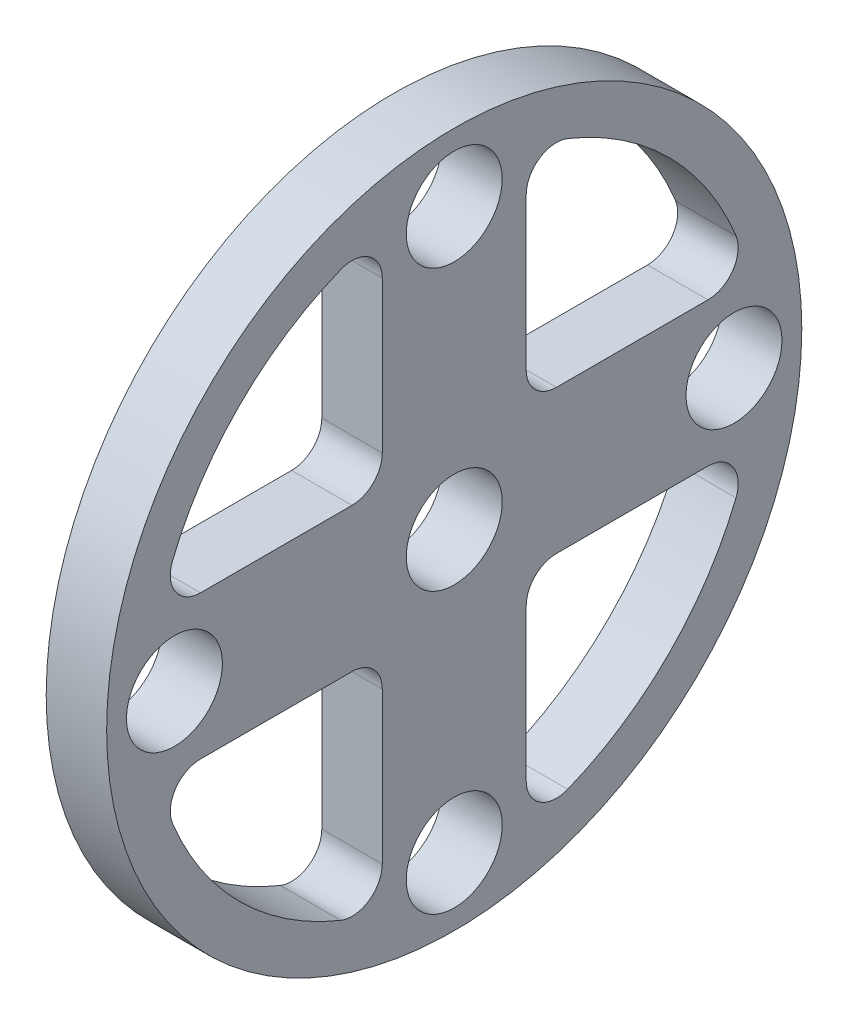
SolidWorks part; units mm, degrees
ref_plane "Front Plane" through (0, 0, 0) normal (0, 0, 1) x (1, 0, 0)
ref_plane "Top Plane" through (0, 0, 0) normal (0, 1, 0) x (1, 0, 0)
ref_plane "Right Plane" through (0, 0, 0) normal (1, 0, 0) x (0, 0, -1)
sketch "Sketch1" plane through (0, 0, 0) normal (1, 0, 0) x (0, 0, -1)
  line L0 (0, 0) -> (0, 1.0694) construction
  line L1 (4.7625, 6.7625) -> (4.7625, 16.7892)
  line L2 (16.7892, 4.7625) -> (6.7625, 4.7625)
  line L3 (6.7625, -4.7625) -> (16.7892, -4.7625)
  line L4 (4.7625, -16.7892) -> (4.7625, -6.7625)
  line L5 (-4.7625, -6.7625) -> (-4.7625, -16.7892)
  line L6 (-16.7892, -4.7625) -> (-6.7625, -4.7625)
  line L7 (-6.7625, 4.7625) -> (-16.7892, 4.7625)
  line L8 (-4.7625, 16.7892) -> (-4.7625, 6.7625)
  circle A0 centre (0, 0) radius 3.175
  circle A1 centre (0, 18.5125) radius 1.5875 construction
  circle A2 centre (0, 18.5125) radius 3.175
  circle A3 centre (0, 0) radius 23
  circle A4 centre (-18.5125, 0) radius 1.5875 construction
  circle A5 centre (-18.5125, 0) radius 3.175
  circle A6 centre (0, -18.5125) radius 1.5875 construction
  circle A7 centre (0, -18.5125) radius 3.175
  circle A8 centre (18.5125, 0) radius 1.5875 construction
  circle A9 centre (18.5125, 0) radius 3.175
  circle A10 centre (0, 0) radius 20.1 construction
  circle A11 centre (0, 0) radius 18.5125 construction
  arc A13 (6.7625, -4.7625) -> (4.7625, -6.7625) centre (6.7625, -6.7625) ccw
  arc A15 (16.7892, -4.7625) -> (18.6444, -7.5097) centre (16.7892, -6.7625) cw
  arc A16 (4.7625, 6.7625) -> (6.7625, 4.7625) centre (6.7625, 6.7625) ccw
  arc A17 (7.5097, 18.6444) -> (18.6444, 7.5097) centre (0, 0) cw
  arc A18 (4.7625, 16.7892) -> (7.5097, 18.6444) centre (6.7625, 16.7892) cw
  arc A19 (16.7892, 4.7625) -> (18.6444, 7.5097) centre (16.7892, 6.7625) ccw
  arc A20 (18.6444, -7.5097) -> (7.5097, -18.6444) centre (0, 0) cw
  arc A21 (4.7625, -16.7892) -> (7.5097, -18.6444) centre (6.7625, -16.7892) ccw
  arc A22 (-4.7625, -6.7625) -> (-6.7625, -4.7625) centre (-6.7625, -6.7625) ccw
  arc A23 (-4.7625, -16.7892) -> (-7.5097, -18.6444) centre (-6.7625, -16.7892) cw
  arc A24 (-7.5097, -18.6444) -> (-18.6444, -7.5097) centre (0, 0) cw
  arc A25 (-16.7892, -4.7625) -> (-18.6444, -7.5097) centre (-16.7892, -6.7625) ccw
  arc A26 (-6.7625, 4.7625) -> (-4.7625, 6.7625) centre (-6.7625, 6.7625) ccw
  arc A27 (-16.7892, 4.7625) -> (-18.6444, 7.5097) centre (-16.7892, 6.7625) cw
  arc A28 (-18.6444, 7.5097) -> (-7.5097, 18.6444) centre (0, 0) cw
  arc A29 (-4.7625, 16.7892) -> (-7.5097, 18.6444) centre (-6.7625, 16.7892) ccw
  dimension "D2" = 3.175
  dimension "D3" = 6.35
  dimension "D4" = 46
  dimension "D5" = 40.2
  dimension "D6" = 37.025
  dimension "D7" = 4
  dimension "D8" = 2
  dimension "D9" = 2
  dimension "D10" = 2
extrude "Boss-Extrude1" add sketch "Sketch1" along normal blind 4
